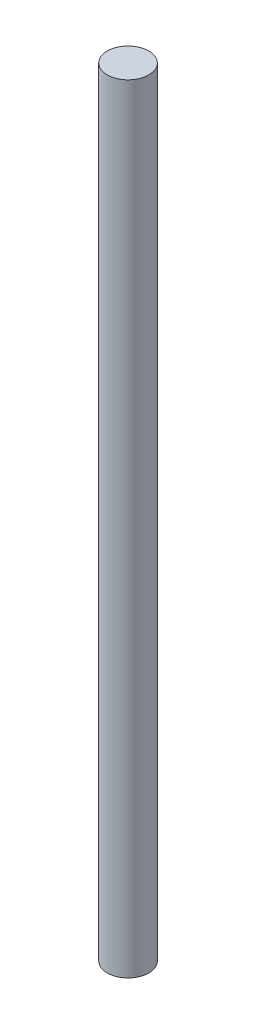
SolidWorks part; units mm, degrees
ref_plane "Front" through (0, 0, 0) normal (0, 0, 1) x (1, 0, 0)
ref_plane "Top" through (0, 0, 0) normal (0, 1, 0) x (1, 0, 0)
ref_plane "Right" through (0, 0, 0) normal (1, 0, 0) x (0, 0, -1)
sketch "Sketch1" plane through (0, 0, 0) normal (0, 1, 0) x (1, 0, 0)
  circle A0 centre (0, 0) radius 4
  dimension "D1" = 8
extrude "Boss-Extrude1" add sketch "Sketch1" along normal blind 150
